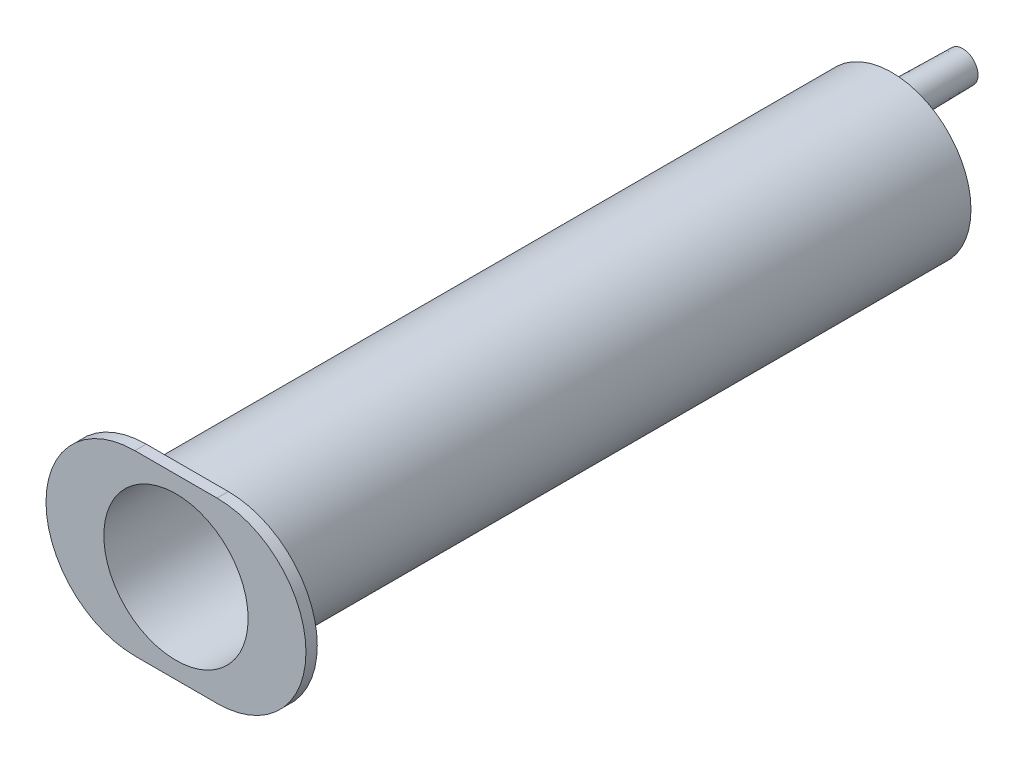
SolidWorks part; units mm, degrees
ref_plane "Front Plane" through (0, 0, 0) normal (0, 0, 1) x (1, 0, 0)
ref_plane "Top Plane" through (0, 0, 0) normal (0, 1, 0) x (1, 0, 0)
ref_plane "Right Plane" through (0, 0, 0) normal (1, 0, 0) x (0, 0, -1)
sketch "Sketch1" plane through (0, 0, 0) normal (0, 0, 1) x (1, 0, 0)
  circle A0 centre (0, 0) radius 10.5
  dimension "D1" = 21
extrude "Boss-Extrude1" add sketch "Sketch1" along normal blind 95
sketch "Sketch2" plane through (0, 0, 95) normal (0, 0, 1) x (1, 0, 0)
  line L0 (5.45, 0) -> (-5.45, 0) construction
  line L1 (5.45, -11.8) -> (-5.45, -11.8)
  line L2 (5.45, 11.8) -> (-5.45, 11.8)
  arc A0 (5.45, -11.8) -> (5.45, 11.8) centre (5.45, 0) ccw
  arc A1 (-5.45, 11.8) -> (-5.45, -11.8) centre (-5.45, 0) ccw
  point P2 (0, 0)
  dimension "D2" = 10.9
  dimension "D1" = 23.6
extrude "Boss-Extrude2" add sketch "Sketch2" against normal blind 1.5
sketch "Sketch3" plane through (0, 0, 0) normal (0, 0, -1) x (-1, 0, 0)
  line L0 (0, -1000) -> (0, 49000) construction
  circle A0 centre (0, 6.5) radius 2.2
  dimension "D1" = 4.4
  dimension "D2" = 6.5
extrude "Boss-Extrude3" add sketch "Sketch3" along normal blind 9.4 draft 1
sketch "Sketch4" plane through (0, 0, 95) normal (0, 0, 1) x (1, 0, 0)
  circle A0 centre (0, 0) radius 9.575
  dimension "D1" = 19.15
extrude "Cut-Extrude1" cut sketch "Sketch4" along direction (0, 0, 1) on the side against the normal offset from surface (93.5 mm away) 1.5
sketch "Sketch5" plane through (0, 0, -9.4) normal (0, 0, -1) x (-1, 0, 0)
  circle A0 centre (0, 6.5) radius 1
  dimension "D1" = 2
extrude "Cut-Extrude2" cut sketch "Sketch5" against normal through all
